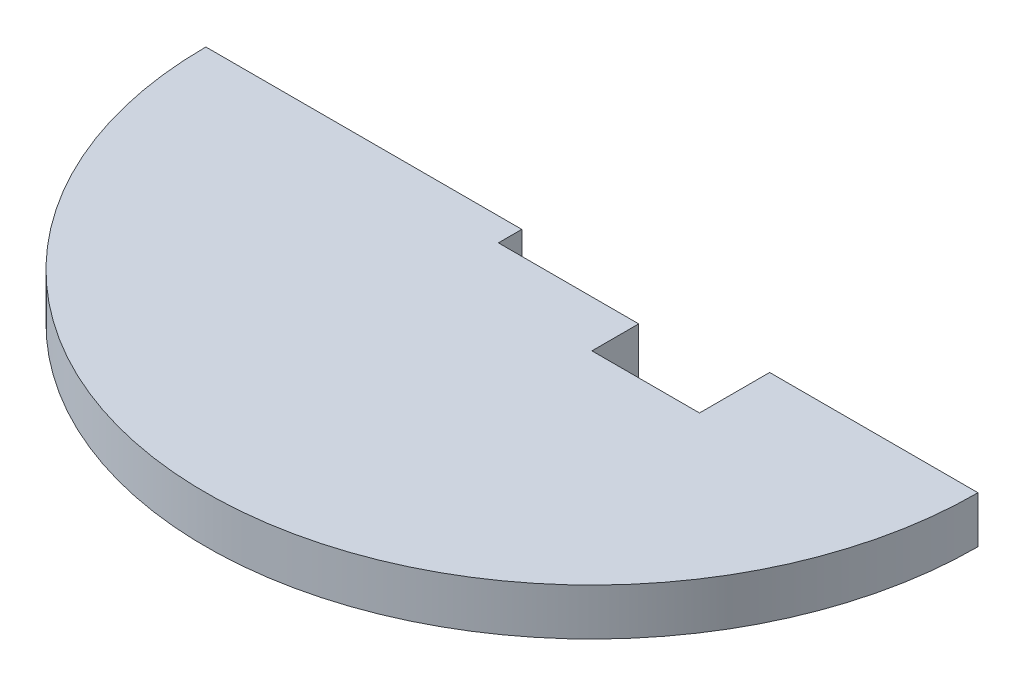
SolidWorks part; units mm, degrees
ref_plane "Front Plane" through (0, 0, 0) normal (0, 0, 1) x (1, 0, 0)
ref_plane "Top Plane" through (0, 0, 0) normal (0, 1, 0) x (1, 0, 0)
ref_plane "Right Plane" through (0, 0, 0) normal (1, 0, 0) x (0, 0, -1)
sketch "Sketch1" plane through (0, 0, 0) normal (0, 1, 0) x (1, 0, 0)
  circle A0 centre (0, 0) radius 82.55
  dimension "D1" = 165.1
extrude "Boss-Extrude1" add sketch "Sketch1" along normal blind 10
extrude "Cut-Extrude1" cut sketch "Sketch2" against normal blind 13
sketch "Sketch2" plane through (0, 13, 0) normal (0, 1, 0) x (1, 0, 0)
  line L1 (-15, 5) -> (15, 5)
  line L2 (-15, 5) -> (-15, -5)
  line L3 (-15, -5) -> (15, -5)
  line L4 (15, 5) -> (15, -5)
  line L5 (-15, 5) -> (15, -5) construction
  line L6 (-15, -5) -> (15, 5) construction
  point P0 (0, 0)
sketch "Sketch3" plane through (0, 10, 0) normal (0, 1, 0) x (1, 0, 0)
  line L0 (-82.55, 0) -> (82.55, 0)
  circle A0 centre (0, 0) radius 82.55 construction
  arc A1 (82.55, 0) -> (-82.55, 0) centre (0, 0) ccw
  line M1 (15, 5) -> (15, -5)
  line M3 (-15, -5) -> (-15, 5)
  line M4 (-15, 5) -> (15, 5)
  circle M5 centre (0, 0) radius 82.55
extrude "Cut-Extrude2" cut sketch "Sketch3" against normal blind 10 contours L0 M5 M3 M4 M1
extrude "Cut-Extrude4" cut sketch "Sketch5" against normal blind 10
sketch "Sketch5" plane through (0, 10, 0) normal (0, 1, 0) x (1, 0, 0)
  line L0 (15, 0) -> (0, 0) construction
  line L1 (15, 15) -> (38, 15)
  line L2 (15, 15) -> (15, -15)
  line L3 (15, -15) -> (38, -15)
  line L4 (38, 15) -> (38, -15)
